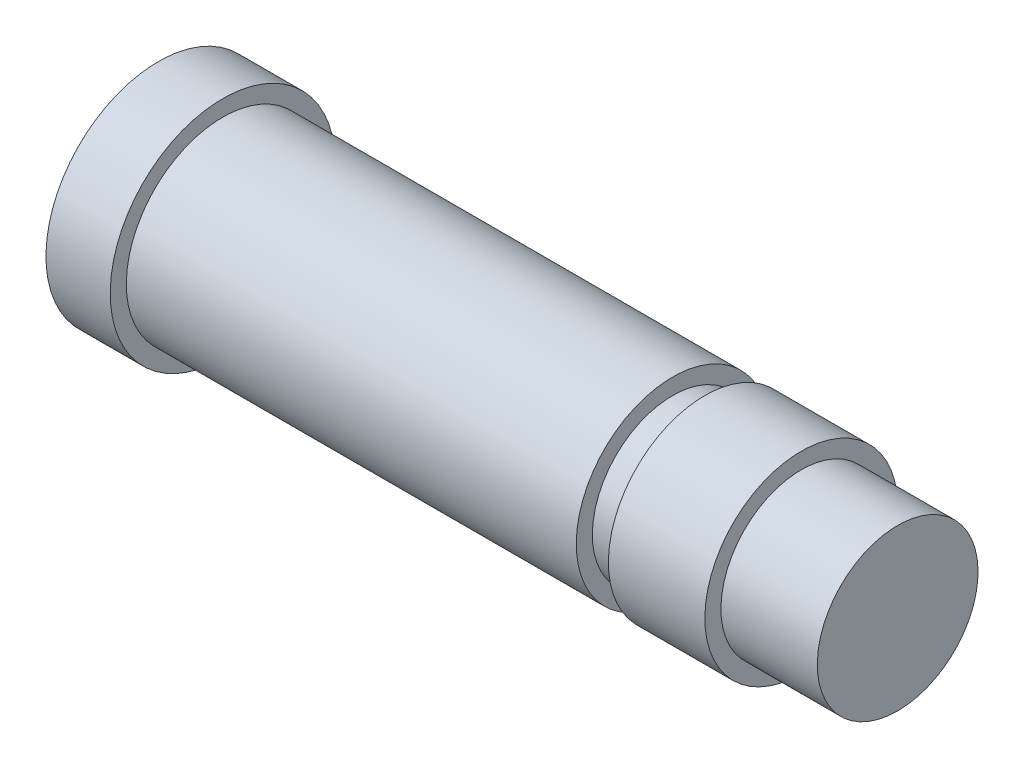
SolidWorks part; units mm, degrees
ref_plane "Front Plane" through (0, 0, 0) normal (0, 0, 1) x (1, 0, 0)
ref_plane "Top Plane" through (0, 0, 0) normal (0, 1, 0) x (1, 0, 0)
ref_plane "Right Plane" through (0, 0, 0) normal (1, 0, 0) x (0, 0, -1)
sketch "Sketch1" plane through (0, 0, 0) normal (0, 0, 1) x (1, 0, 0)
  line L0 (0, 0) -> (40, 0)
  line L1 (40, 5) -> (40, 6)
  line L2 (40, 6) -> (34, 6)
  line L3 (4, 6) -> (4, 7)
  line L4 (4, 7) -> (0, 7)
  line L5 (0, 7) -> (0, 0)
  line L6 (34, 6) -> (34, 5)
  line L7 (34, 5) -> (32, 5)
  line L8 (32, 5) -> (32, 6)
  line L9 (32, 6) -> (4, 6)
  line L10 (40, 5) -> (46, 5)
  line L11 (46, 5) -> (46, 0)
  line L12 (46, 0) -> (40, 0)
  point P14 (40, 5.5)
  dimension "D1" = 6
  dimension "D2" = 7
  dimension "D3" = 4
  dimension "D4" = 36
  dimension "D5" = 28
  dimension "D6" = 2
  dimension "D7" = 5
  dimension "D8" = 6
  dimension "D9" = 6
revolve "Revolve1" add sketch "Sketch1" angle 360 about L0
